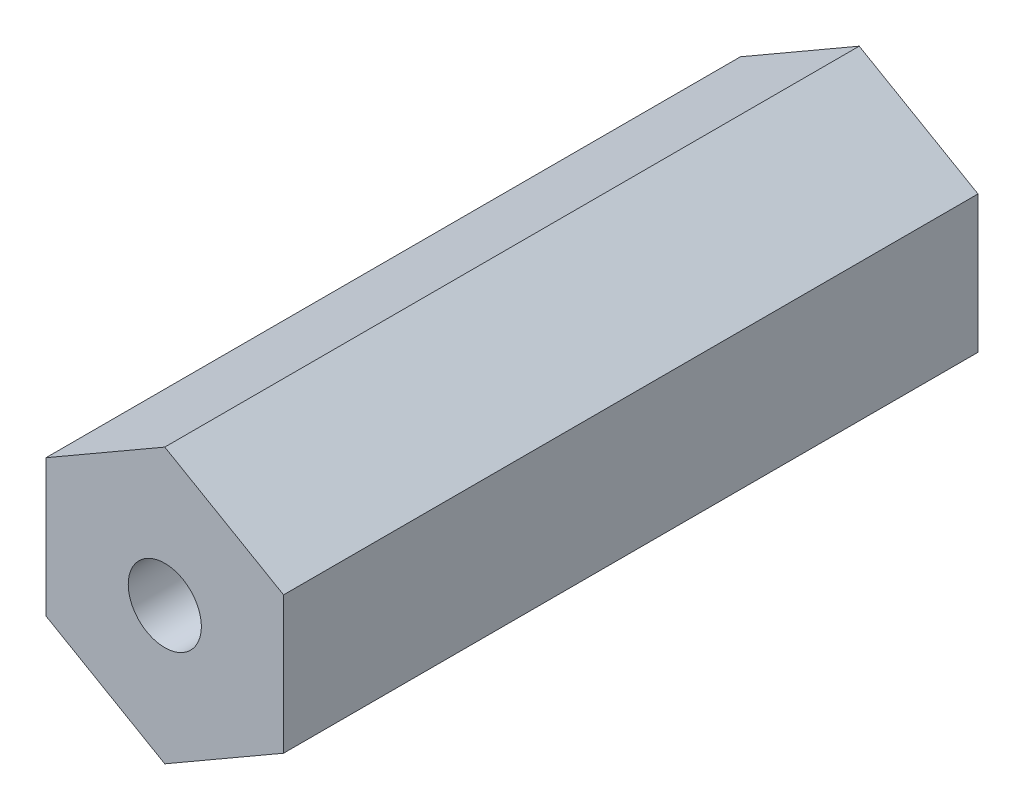
SolidWorks part; units mm, degrees
ref_plane "Front Plane" through (0, 0, 0) normal (0, 0, 1) x (1, 0, 0)
ref_plane "Top Plane" through (0, 0, 0) normal (0, 1, 0) x (1, 0, 0)
ref_plane "Right Plane" through (0, 0, 0) normal (1, 0, 0) x (0, 0, -1)
sketch "Sketch1" plane through (0, 0, 0) normal (0, 0, 1) x (1, 0, 0)
  line L1 (10.3187, -5.9575) -> (10.3187, 5.9575)
  line L2 (10.3187, 5.9575) -> (0, 11.9151)
  line L3 (0, 11.9151) -> (-10.3188, 5.9575)
  line L4 (-10.3188, 5.9575) -> (-10.3187, -5.9575)
  line L5 (-10.3187, -5.9575) -> (0, -11.9151)
  line L6 (0, -11.9151) -> (10.3187, -5.9575)
  circle A0 centre (0, 0) radius 10.3187 construction
  circle A1 centre (0, 0) radius 3.175
  point P1 (10.3187, 0)
  dimension "D2" = 6.35
  dimension "D1" = 20.6375
extrude "Boss-Extrude1" add sketch "Sketch1" along normal blind 60.325
